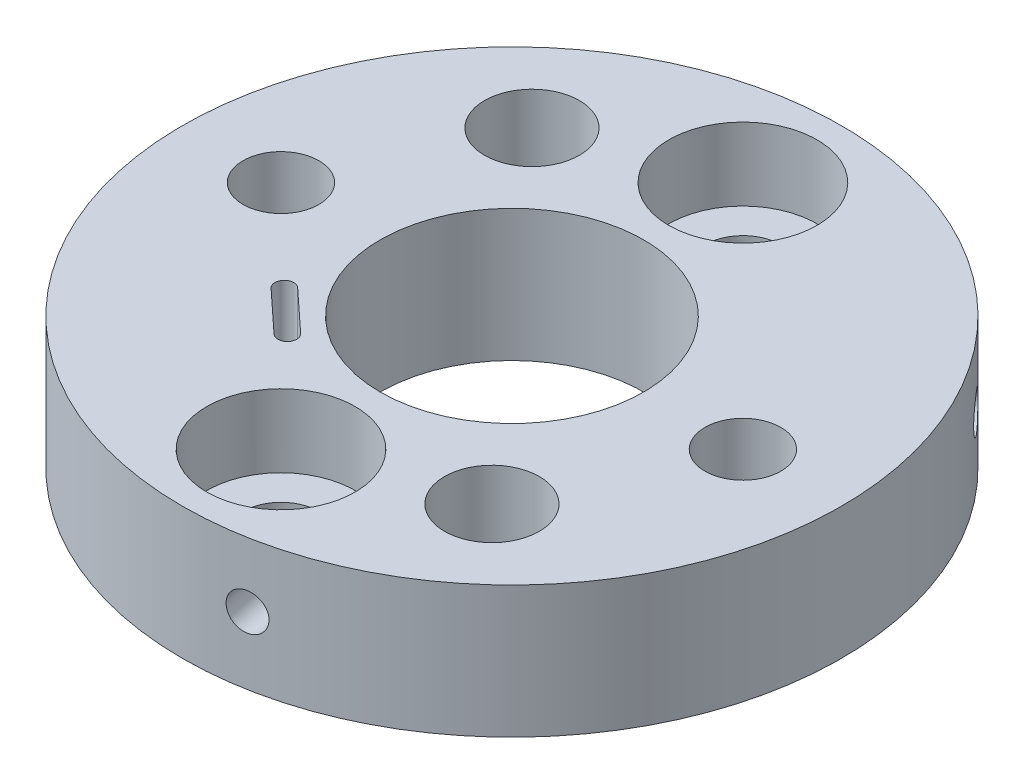
SolidWorks part; units mm, degrees
ref_plane "Front Plane" through (0, 0, 0) normal (0, 0, 1) x (1, 0, 0)
ref_plane "Top Plane" through (0, 0, 0) normal (0, 1, 0) x (1, 0, 0)
ref_plane "Right Plane" through (0, 0, 0) normal (1, 0, 0) x (0, 0, -1)
sketch "Sketch1" plane through (0, 0, 0) normal (0, 1, 0) x (1, 0, 0)
  circle A0 centre (0, 0) radius 15.875
  dimension "D1" = 31.75
extrude "Boss-Extrude1" add sketch "Sketch1" along normal blind 6.35
sketch "Sketch2" plane through (0, 6.35, 0) normal (0, 1, 0) x (1, 0, 0)
  circle A0 centre (0, 0) radius 6.35
  dimension "D1" = 12.7
extrude "Cut-Extrude1" cut sketch "Sketch2" against normal through all
sketch "Sketch5" plane through (0, 6.35, 0) normal (0, 1, 0) x (1, 0, 0)
  line L0 (0, 0) -> (0, 11.1252)
  line L1 (0, 0) -> (11.1252, 0)
  dimension "D1" = 11.1252
  dimension "D2" = 11.1252
hole_wizard "CBORE for #6 Socket Head Cap Screw1" positions "Sketch6" profile "Sketch7" counterbore size "#6" standard "ANSI Inch" end condition through all
sketch "Sketch6" plane through (0, 6.35, 0) normal (0, 1, 0) x (1, 0, 0)
  point P0 (0, 11.1252)
sketch "Sketch7" plane through (0, 6.35, -11.1252) normal (1, 0, 0) x (0, 0, 1)
  line L0 (0, 0) -> (0, 6.35)
  line L1 (0, 6.35) -> (1.8288, 6.35)
  line L3 (1.8288, 6.35) -> (1.8288, 3.5052)
  line L4 (1.8288, 3.5052) -> (3.5725, 3.5052)
  line L5 (3.5725, 3.5052) -> (3.5725, 0)
  line L7 (3.5725, 0) -> (0, 0)
  line L11 (0, -6.35) -> (0, 107.95) construction
  dimension "Thru Hole Dia." = 3.6576
  dimension "Thru Hole Depth" = 6.35
  dimension "C'Bore Dia." = 7.145
  dimension "C'Bore Depth" = 3.5052
pattern_circular "CirPattern1" count 2 every 180 about axis through (0, 0, 0) along (0, 1, 0) of "CBORE for #6 Socket Head Cap Screw1"
hole_wizard "#6 Clearance Hole1" [suppressed] positions "Sketch9" profile "Sketch10" hole size "#6" standard "ANSI Inch"
sketch "Sketch9" plane through (0, 6.35, 0) normal (0, 1, 0) x (1, 0, 0)
  point P0 (11.1252, 0)
sketch "Sketch10" plane through (11.1252, 6.35, 0) normal (1, 0, 0) x (0, 0, 1)
  line L0 (0, 0) -> (0, 6.35)
  line L1 (0, 6.35) -> (2.1828, 6.35)
  line L2 (1.8288, 5.9428) -> (1.8288, 0)
  line L5 (1.8288, 0) -> (0, 0)
  line L7 (2.1828, 6.35) -> (1.8288, 5.9428)
  line L8 (-2.1828, 6.35) -> (-1.8288, 5.9428) construction
  line L11 (0, -6.35) -> (0, 107.95) construction
  dimension "Thru Hole Dia." = 3.6576
  dimension "Thru Hole Depth" = 6.35
  dimension "Far C'Sink Dia." = 4.3656
  dimension "Far C'Sink Angle" = 82
pattern_circular "CirPattern2" [suppressed] count 2 over 360
sketch "Sketch11" plane through (0, 6.35, 0) normal (0, 1, 0) x (1, 0, 0)
  line L0 (0, 0) -> (-7.3609, 8.325)
  circle A0 centre (-7.3609, 8.325) radius 2.286
  dimension "D2" = 4.572
  dimension "D1" = 11.1125
extrude "Cut-Extrude2" cut sketch "Sketch11" against normal through all contours A0
pattern_circular "CirPattern3" count 2 over 360 about axis through (0, 0, 0) along (0, 1, 0) of "Cut-Extrude2"
ref_plane "Plane1" through (0, 3.175, 0) normal (0, -1, 0) x (-1, 0, 0)
ref_plane "Plane2" through (0, 0, 15.875) normal (0, 0, 1) x (1, 0, 0)
hole_wizard "Tap Drill for #2-56 Tap3" positions "3DSketch1" profile "Sketch16" hole size "#2-56" standard "ANSI Inch"
sketch3d "3DSketch1"
  point P0 (12.0931, 3.245, -10.2845)
sketch "Sketch16" plane through (12.0931, 3.245, -10.2845) normal (0, 1, 0) x (-0.6478, 0, -0.7618)
  line L0 (0, 0) -> (0, 7.096)
  line L1 (0, 7.096) -> (0.889, 6.35)
  line L2 (0.889, 6.35) -> (0.889, 0)
  line L5 (0.889, 0) -> (0, 0)
  line L10 (0, 7.096) -> (-0.889, 6.35) construction
  line L11 (0, -6.35) -> (0, 107.95) construction
  dimension "Hole Dia." = 1.778
  dimension "Hole Depth" = 6.35
  dimension "Drill Angle" = 100
pattern_circular "CirPattern4" count 3 every 120 about axis through (0, 6.35, 0) along (0, -1, 0) of "Tap Drill for #2-56 Tap3"
sketch "Sketch17" plane through (0, 6.35, 0) normal (0, 1, 0) x (1, 0, 0)
  line L0 (-4.6609, -6.1577) -> (-6.6475, -4.3143) construction
  line L1 (-4.9691, -6.4899) -> (-6.9558, -4.6465)
  line L2 (-4.3526, -5.8255) -> (-6.3392, -3.982)
  arc A0 (-4.9691, -6.4899) -> (-4.3526, -5.8255) centre (-4.6609, -6.1577) ccw
  arc A1 (-6.3392, -3.982) -> (-6.9558, -4.6465) centre (-6.6475, -4.3143) ccw
  point P4 (-5.6542, -5.236)
extrude "Cut-Extrude3" cut sketch "Sketch17" against normal through all
sketch "Sketch19" plane through (0, 0, 0) normal (0, -1, 0) x (1, 0, 0)
  point P0 (11.1252, 0)
hole_wizard "CBORE for #6 Socket Head Cap Screw2" positions "3DSketch3" profile "Sketch21" counterbore size "#6" standard "ANSI Inch" end condition through all
sketch3d "3DSketch3"
  point P0 (11.1252, 0, 0)
sketch "Sketch21" plane through (11.1252, 0, 0) normal (1, 0, 0) x (0, 0, -1)
  line L0 (0, 0) -> (0, 6.35)
  line L1 (0, 6.35) -> (1.8288, 6.35)
  line L3 (1.8288, 6.35) -> (1.8288, 3.5052)
  line L4 (1.8288, 3.5052) -> (3.5725, 3.5052)
  line L5 (3.5725, 3.5052) -> (3.5725, 0)
  line L7 (3.5725, 0) -> (0, 0)
  line L11 (0, -6.35) -> (0, 107.95) construction
  dimension "Thru Hole Dia." = 3.6576
  dimension "Thru Hole Depth" = 6.35
  dimension "C'Bore Dia." = 7.145
  dimension "C'Bore Depth" = 3.5052
pattern_circular "CirPattern5" count 2 every 180 about axis through (0, 0, 0) along (0, 1, 0) of "CBORE for #6 Socket Head Cap Screw2"
